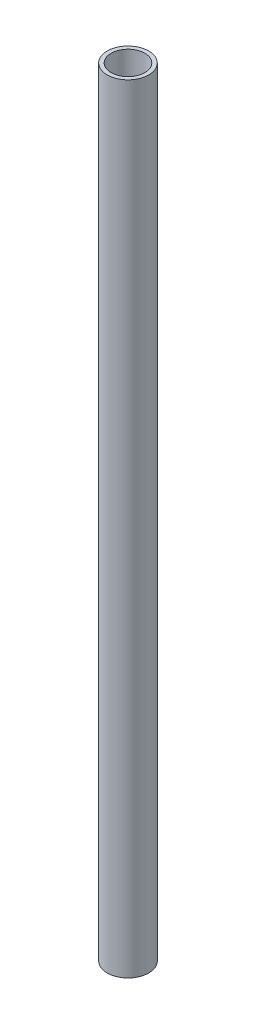
SolidWorks part; units mm, degrees
ref_plane "Front Plane" through (0, 0, 0) normal (0, 0, 1) x (1, 0, 0)
ref_plane "Top Plane" through (0, 0, 0) normal (0, 1, 0) x (1, 0, 0)
ref_plane "Right Plane" through (0, 0, 0) normal (1, 0, 0) x (0, 0, -1)
sketch "Croquis_tubo" plane through (0, 0, 0) normal (0, 1, 0) x (1, 0, 0)
  circle A0 centre (0, 0) radius 8
  circle A1 centre (0, 0) radius 6.5
  dimension "D1" = 16
  dimension "D2" = 13
extrude "Tubo" add sketch "Croquis_tubo" along normal blind 300
